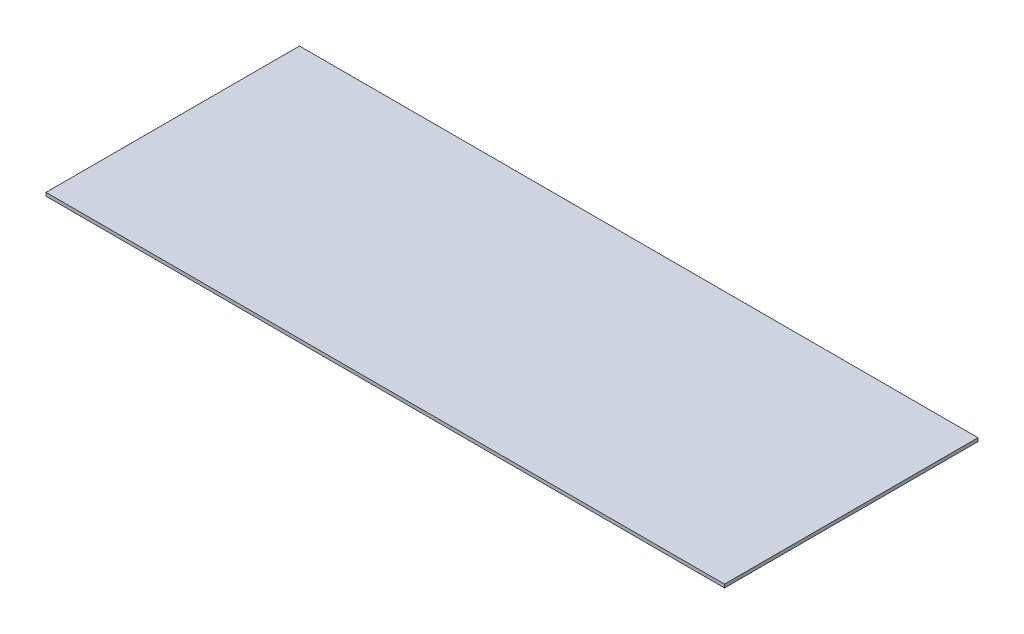
SolidWorks part; units mm, degrees
material "Glas"
ref_plane "Ebene vorne" through (0, 0, 0) normal (0, 0, 1) x (1, 0, 0)
ref_plane "Ebene oben" through (0, 0, 0) normal (0, 1, 0) x (1, 0, 0)
ref_plane "Ebene rechts" through (0, 0, 0) normal (1, 0, 0) x (0, 0, -1)
sketch "Skizze1" plane through (0, 0, 0) normal (0, 0, 1) x (1, 0, 0)
  line L0 (401.5, 0) -> (-401.5, 0)
  line L1 (401.5, 4) -> (-401.5, 4)
  line L2 (-401.5, 4) -> (-401.5, 0)
  line L3 (401.5, 0) -> (401.5, 4)
  point P4 (0, 0)
  point P8 (0, 4)
  dimension "D1" = 4
  dimension "D2" = 803
extrude "Aufsatz-Linear austragen1" add sketch "Skizze1" along normal blind 300
equation "\"wall_thickness\"= 4mm"
equation "\"wall_height\"= 300"
equation "\"D1@Skizze1\"=\"wall_thickness\""
equation "\"D1@Aufsatz-Linear austragen1\"=\"wall_height\""
equation "\"edge_length\"= 800mm"
equation "\"coldplate_circumference\"= 4*\"edge_length\""
equation "\"L-profile_width\"= 20mm"
equation "\"L-profile_thickness\"= 1.5mm"
equation "\"extrusion_width\"= 40mm"
equation "\"D2@Skizze1\"=\"edge_length\" + \"L-profile_thickness\"*2"
